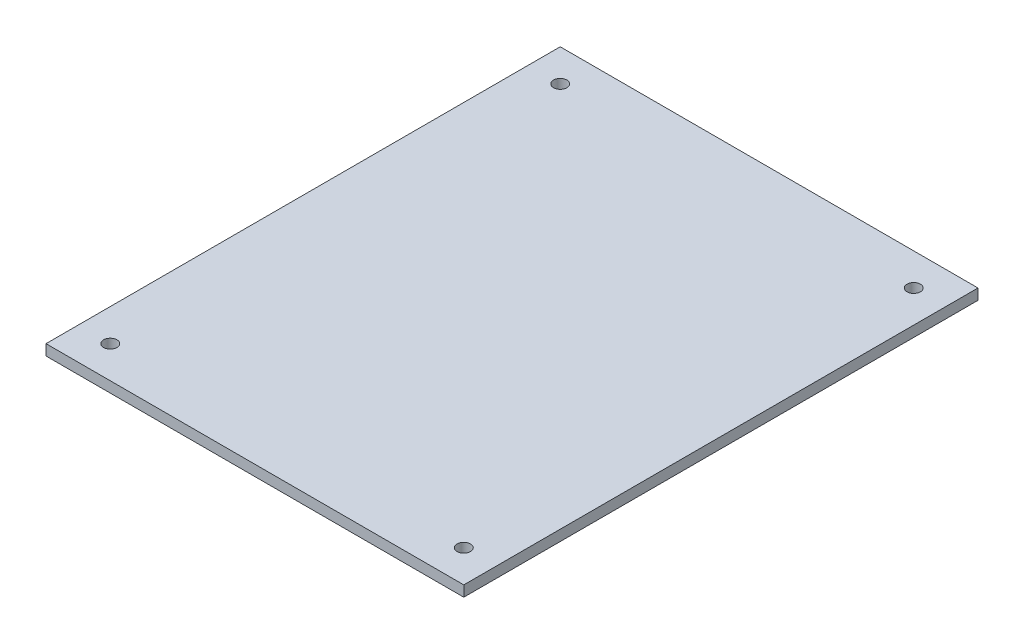
SolidWorks part; units mm, degrees
ref_plane "Front Plane" through (0, 0, 0) normal (0, 0, 1) x (1, 0, 0)
ref_plane "Top Plane" through (0, 0, 0) normal (0, 1, 0) x (1, 0, 0)
ref_plane "Right Plane" through (0, 0, 0) normal (1, 0, 0) x (0, 0, -1)
sketch "Sketch1" plane through (0, 0, 0) normal (0, 1, 0) x (1, 0, 0)
  line L0 (-57.2299, 28.1542) -> (-49.6099, 28.1542) construction
  line L1 (-57.2299, 68.9604) -> (41.8301, 68.9604)
  line L2 (-57.2299, 68.9604) -> (-57.2299, -52.9596)
  line L3 (-57.2299, -52.9596) -> (41.8301, -52.9596)
  line L4 (41.8301, 68.9604) -> (41.8301, -52.9596)
  line L5 (-49.6099, 61.3404) -> (34.2101, 61.3404) construction
  line L6 (-49.6099, 61.3404) -> (-49.6099, -45.3396) construction
  line L7 (-49.6099, -45.3396) -> (34.2101, -45.3396) construction
  line L8 (34.2101, 61.3404) -> (34.2101, -45.3396) construction
  line L9 (34.2101, 28.1542) -> (41.8301, 28.1542) construction
  line L10 (-13.0489, 68.9604) -> (-13.0489, 61.3404) construction
  line L11 (-1.5124, -45.3396) -> (-1.5124, -52.9596) construction
  circle A0 centre (-49.6099, 61.3404) radius 1.5875
  circle A1 centre (34.2101, 61.3404) radius 1.5875
  circle A2 centre (-49.6099, -45.3396) radius 1.5875
  circle A3 centre (34.2101, -45.3396) radius 1.5875
  dimension "D5" = 3.175
  dimension "D1" = 121.92
  dimension "D2" = 99.06
  dimension "D3" = 106.68
  dimension "D4" = 83.82
extrude "Boss-Extrude1" add sketch "Sketch1" along normal blind 2.54
